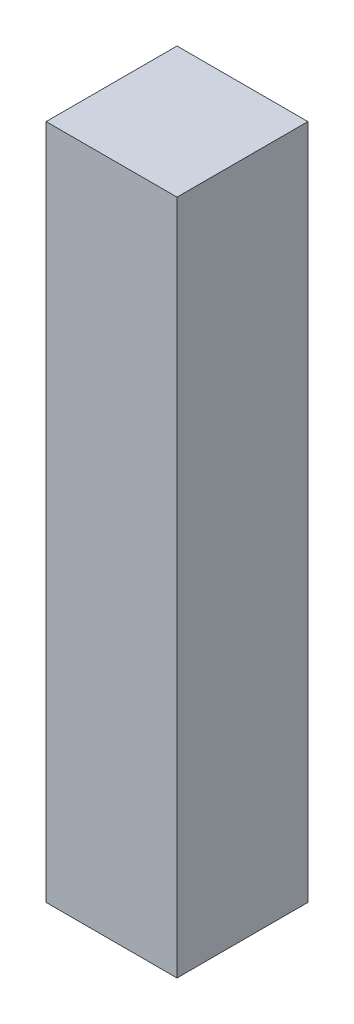
SolidWorks part; units mm, degrees
ref_plane "Front Plane" through (0, 0, 0) normal (0, 0, 1) x (1, 0, 0)
ref_plane "Top Plane" through (0, 0, 0) normal (0, 1, 0) x (1, 0, 0)
ref_plane "Right Plane" through (0, 0, 0) normal (1, 0, 0) x (0, 0, -1)
sketch "Sketch1" plane through (0, 0, 0) normal (0, 1, 0) x (1, 0, 0)
  line L1 (0, 0) -> (19.05, 0)
  line L2 (0, 0) -> (0, 19.05)
  line L3 (0, 19.05) -> (19.05, 19.05)
  line L4 (19.05, 0) -> (19.05, 19.05)
  dimension "D1" = 19.05
  dimension "D2" = 19.05
extrude "Boss-Extrude1" add sketch "Sketch1" along normal blind 98.425
